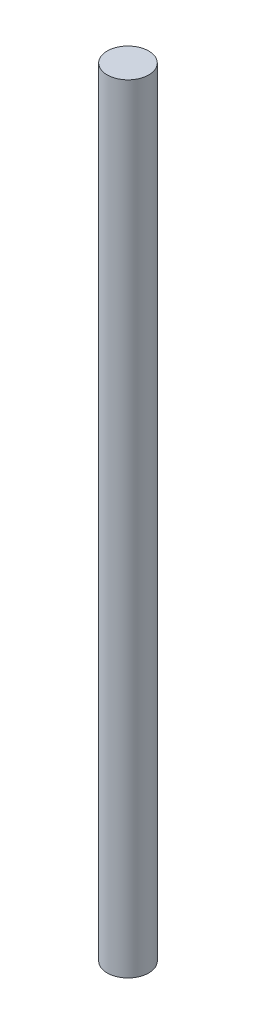
SolidWorks part; units mm, degrees
ref_plane "Front Plane" through (0, 0, 0) normal (0, 0, 1) x (1, 0, 0)
ref_plane "Top Plane" through (0, 0, 0) normal (0, 1, 0) x (1, 0, 0)
ref_plane "Right Plane" through (0, 0, 0) normal (1, 0, 0) x (0, 0, -1)
sketch "Sketch1" plane through (0, 0, 0) normal (0, 1, 0) x (1, 0, 0)
  circle A0 centre (0, 0) radius 8
  dimension "D1" = 16
extrude "Boss-Extrude1" add sketch "Sketch1" along normal blind 300
